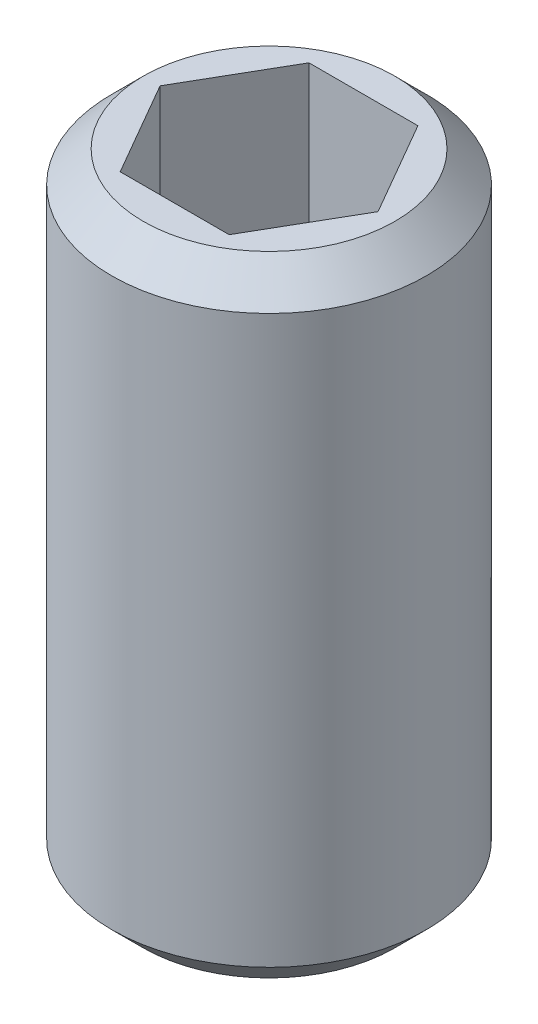
SolidWorks part; units mm, degrees
ref_plane "Płaszczyzna przednia" through (0, 0, 0) normal (0, 0, 1) x (1, 0, 0)
ref_plane "Płaszczyzna górna" through (0, 0, 0) normal (0, 1, 0) x (1, 0, 0)
ref_plane "Płaszczyzna prawa" through (0, 0, 0) normal (1, 0, 0) x (0, 0, -1)
sketch "Szkic1" plane through (0, 0, 0) normal (0, 1, 0) x (1, 0, 0)
  circle A0 centre (42.2075, 13.1133) radius 2.5
  dimension "D1" = 5
extrude "Dodanie-wyciągnięcie1" add sketch "Szkic1" along normal blind 10
sketch "Szkic2" plane through (0, 10, 0) normal (0, 1, 0) x (1, 0, 0)
  line L1 (43.9396, 13.1133) -> (43.0736, 14.6133)
  line L2 (43.0736, 14.6133) -> (41.3415, 14.6133)
  line L3 (41.3415, 14.6133) -> (40.4755, 13.1133)
  line L4 (40.4755, 13.1133) -> (41.3415, 11.6133)
  line L5 (41.3415, 11.6133) -> (43.0736, 11.6133)
  line L6 (43.0736, 11.6133) -> (43.9396, 13.1133)
  circle A0 centre (42.2075, 13.1133) radius 1.5 construction
  dimension "D1" = 3
extrude "Wytnij-wyciągnięcie1" cut sketch "Szkic2" against normal blind 3
chamfer "Sfazowanie1" distance 0.5 angle 45 2 edges at (42.2075, 10, -10.6133) (42.2075, 0, -10.6133)
